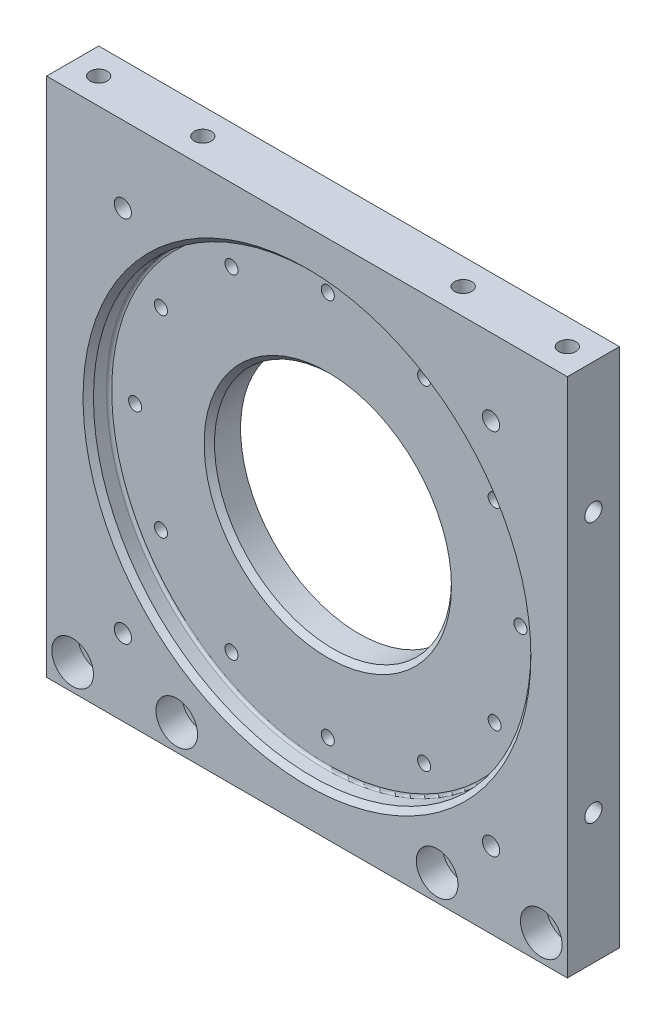
SolidWorks part; units mm, degrees
material "ALUMINIUM,  6082-T6"
ref_plane "Front Plane" through (0, 0, 0) normal (0, 0, 1) x (1, 0, 0)
ref_plane "Top Plane" through (0, 0, 0) normal (0, 1, 0) x (1, 0, 0)
ref_plane "Right Plane" through (0, 0, 0) normal (1, 0, 0) x (0, 0, -1)
sketch "Sketch1" plane through (0, 0, 0) normal (1, 0, 0) x (0, 0, -1)
  line L0 (-5, 50) -> (-5, -50)
  line L2 (-5, -50) -> (5, -50)
  line L8 (5, -50) -> (5, 50)
  line L9 (5, 50) -> (-5, 50)
  line L10 (-5, 50) -> (5, -50) construction
  dimension "D1" = 100
  dimension "D2" = 10
extrude "Boss-Extrude1" add sketch "Sketch1" along normal mid plane 100
sketch "Sketch2" plane through (0, 0, 5) normal (0, 0, 1) x (1, 0, 0)
  circle A0 centre (0, 0) radius 42
  dimension "D1" = 84
extrude "Cut-Extrude1" cut sketch "Sketch2" against normal blind 4
sketch "Sketch4" plane through (0, 0, 1) normal (0, 0, 1) x (1, 0, 0)
  circle A0 centre (0, 0) radius 22.75
  dimension "D1" = 45.5
extrude "Cut-Extrude3" cut sketch "Sketch4" against normal up to next
hole_wizard "M3 Tapped Hole1" positions "Sketch9" profile "Sketch10" tap size "M3" standard "ISO" end condition through all
sketch "Sketch9" plane through (0, 0, 1) normal (0, 0, 1) x (1, 0, 0)
  line L4 (-37, 0) -> (37, 0) construction
  line L5 (18.5, 32.0429) -> (-18.5, -32.0429) construction
  line L6 (-32.0429, 18.5) -> (32.0429, -18.5) construction
  line L7 (0, 37) -> (0, -37) construction
  line L8 (-18.5, 32.0429) -> (18.5, -32.0429) construction
  line L11 (-32.0429, -18.5) -> (32.0429, 18.5) construction
  circle A2 centre (0, 0) radius 37 construction
  circle A3 centre (0, 0) radius 22.75 construction
  point P28 (-37, 0)
  point P29 (37, 0)
  point P30 (18.5, 32.0429)
  point P31 (-32.0429, 18.5)
  point P32 (32.0429, -18.5)
  point P33 (-18.5, -32.0429)
  point P40 (0, 37)
  point P41 (0, -37)
  point P49 (-18.5, 32.0429)
  point P51 (18.5, -32.0429)
  point P53 (32.0429, 18.5)
  point P55 (-32.0429, -18.5)
  dimension "D1" = 30
  dimension "D3" = 74
  dimension "D2" = 30
  dimension "D4" = 30
  dimension "D5" = 30
cosmetic thread "Hole Thread4" parameters "D2"=3
cosmetic thread "Hole Thread6" parameters "D2"=3
cosmetic thread "Hole Thread7" parameters "D2"=3
cosmetic thread "Hole Thread18" parameters "D2"=3
cosmetic thread "Hole Thread25" parameters "D2"=3
cosmetic thread "Hole Thread26" parameters "D2"=3
cosmetic thread "Hole Thread28" parameters "D2"=3
cosmetic thread "Hole Thread30" parameters "D2"=3
cosmetic thread "Hole Thread31" parameters "D2"=3
cosmetic thread "Hole Thread39" parameters "D2"=3
cosmetic thread "Hole Thread40" parameters "D2"=3
cosmetic thread "Hole Thread41" parameters "D2"=3
sketch "Sketch10" plane through (-32.0429, -18.5, 1) normal (1, 0, 0) x (0, -1, 0)
  line L0 (0, 0) -> (0, 6)
  line L1 (0, 6) -> (1.25, 6)
  line L2 (1.25, 6) -> (1.25, 0)
  line L5 (1.25, 0) -> (0, 0)
  line L11 (0, -6.35) -> (0, 107.95) construction
  dimension "Thru Tap Drill Dia." = 2.5
  dimension "Thru Tap Drill Depth" = 6
fillet "Fillet3" radius 0.5 1 edges at (42, 0, 1)
chamfer "Chamfer1" distance 1 angle 45 2 edges at (22.75, 0, 1) (42, 0, 5)
hole_wizard "CBORE for M4 Hex Socket Head Cap Screw1" positions "Sketch11" profile "Sketch12" counterbore size "M4" standard "ISO" end condition through all
sketch "Sketch11" plane through (0, 0, 5) normal (0, 0, 1) x (1, 0, 0)
  line L0 (-45, -45) -> (-25, -45) construction
  line L1 (-25, -45) -> (25, -45) construction
  line L2 (25, -45) -> (45, -45) construction
  line L4 (0, 0) -> (0, -45) construction
  line L6 (50, -50) -> (-50, -50) construction
  line L7 (-50, 50) -> (-50, -50) construction
  point P0 (-45, -45)
  point P2 (-25, -45)
  point P4 (25, -45)
  point P6 (45, -45)
  dimension "D1" = 5
  dimension "D2" = 5
  dimension "D3" = 20
sketch "Sketch12" plane through (-45, -45, 5) normal (1, 0, 0) x (0, -1, 0)
  line L0 (0, 0) -> (0, 10)
  line L1 (0, 10) -> (2.25, 10)
  line L3 (2.25, 10) -> (2.25, 5)
  line L4 (2.25, 5) -> (4, 5)
  line L5 (4, 5) -> (4, 0)
  line L7 (4, 0) -> (0, 0)
  line L11 (0, -6.35) -> (0, 107.95) construction
  dimension "Thru Hole Dia." = 4.5
  dimension "Thru Hole Depth" = 10
  dimension "C'Bore Dia." = 8
  dimension "C'Bore Depth" = 5
hole_wizard "M4 Tapped Hole1" positions "Sketch13" profile "Sketch14" tap size "M4" standard "ISO"
sketch "Sketch13" plane through (0, 50, 0) normal (0, 1, 0) x (1, 0, 0)
  line L0 (-45, 0) -> (-25, 0) construction
  line L1 (-25, 0) -> (25, 0) construction
  line L2 (25, 0) -> (45, 0) construction
  line L4 (-50, 5) -> (-50, -5) construction
  point P0 (-45, 0)
  point P2 (-25, 0)
  point P4 (25, 0)
  point P6 (45, 0)
  dimension "D1" = 20
  dimension "D2" = 5
sketch "Sketch14" plane through (-45, 50, 0) normal (1, 0, 0) x (0, 0, 1)
  line L0 (0, 0) -> (0, 11.9914)
  line L1 (0, 11.9914) -> (1.65, 11)
  line L2 (1.65, 11) -> (1.65, 0)
  line L5 (1.65, 0) -> (0, 0)
  line L10 (0, 11.9914) -> (-1.65, 11) construction
  line L11 (0, -6.35) -> (0, 107.95) construction
  dimension "Tap Drill Dia." = 3.3
  dimension "Tap Drill Depth" = 11
  dimension "Drill Angle" = 118
cosmetic thread "Hole Thread42" parameters "D1"=8, "D2"=4
cosmetic thread "Hole Thread43" parameters "D1"=8, "D2"=4
cosmetic thread "Hole Thread44" parameters "D1"=8, "D2"=4
cosmetic thread "Hole Thread45" parameters "D1"=8, "D2"=4
hole_wizard "M4 Tapped Hole2" positions "Sketch15" profile "Sketch16" tap size "M4" standard "ISO"
sketch "Sketch15" plane through (50, 0, 0) normal (1, 0, 0) x (0, 0, -1)
  line L0 (0, 25) -> (0, -25) construction
  point P0 (0, 25)
  point P2 (0, -25)
  dimension "D1" = 50
sketch "Sketch16" plane through (50, 25, 0) normal (0, 1, 0) x (0, 0, -1)
  line L0 (0, 0) -> (0, 11.9914)
  line L1 (0, 11.9914) -> (1.65, 11)
  line L2 (1.65, 11) -> (1.65, 0)
  line L5 (1.65, 0) -> (0, 0)
  line L10 (0, 11.9914) -> (-1.65, 11) construction
  line L11 (0, -6.35) -> (0, 107.95) construction
  dimension "Tap Drill Dia." = 3.3
  dimension "Tap Drill Depth" = 11
  dimension "Drill Angle" = 118
cosmetic thread "Hole Thread46" parameters "D1"=8, "D2"=4
cosmetic thread "Hole Thread47" parameters "D1"=8, "D2"=4
hole_wizard "M4 Tapped Hole3" positions "Sketch17" profile "Sketch18" tap size "M4" standard "ISO"
sketch "Sketch17" plane through (-50, 0, 0) normal (-1, 0, 0) x (0, 0, 1)
  point P0 (0, 25)
  point P3 (0, -25)
sketch "Sketch18" plane through (-50, 25, 0) normal (0, 1, 0) x (0, 0, 1)
  line L0 (0, 0) -> (0, 11.9914)
  line L1 (0, 11.9914) -> (1.65, 11)
  line L2 (1.65, 11) -> (1.65, 0)
  line L5 (1.65, 0) -> (0, 0)
  line L10 (0, 11.9914) -> (-1.65, 11) construction
  line L11 (0, -6.35) -> (0, 107.95) construction
  dimension "Tap Drill Dia." = 3.3
  dimension "Tap Drill Depth" = 11
  dimension "Drill Angle" = 118
cosmetic thread "Hole Thread48" parameters "D1"=8, "D2"=4
cosmetic thread "Hole Thread49" parameters "D1"=8, "D2"=4
hole_wizard "M4 Tapped Hole4" positions "Sketch19" profile "Sketch20" tap size "M4" standard "ISO" end condition through all
sketch "Sketch19" plane through (0, 0, 5) normal (0, 0, 1) x (1, 0, 0)
  line L0 (35.3553, 35.3553) -> (-35.3553, -35.3553) construction
  line L3 (35.3553, -35.3553) -> (-35.3553, 35.3553) construction
  point P0 (35.3553, -35.3553)
  point P3 (35.3553, 35.3553)
  point P6 (-35.3553, 35.3553)
  point P9 (-35.3553, -35.3553)
  dimension "D1" = 100
sketch "Sketch20" plane through (35.3553, -35.3553, 5) normal (1, 0, 0) x (0, -1, 0)
  line L0 (0, 0) -> (0, 10)
  line L1 (0, 10) -> (1.65, 10)
  line L2 (1.65, 10) -> (1.65, 0)
  line L5 (1.65, 0) -> (0, 0)
  line L11 (0, -6.35) -> (0, 107.95) construction
  dimension "Thru Tap Drill Dia." = 3.3
  dimension "Thru Tap Drill Depth" = 10
cosmetic thread "Hole Thread50" parameters "D2"=4
cosmetic thread "Hole Thread51" parameters "D2"=4
cosmetic thread "Hole Thread52" parameters "D2"=4
cosmetic thread "Hole Thread53" parameters "D2"=4
